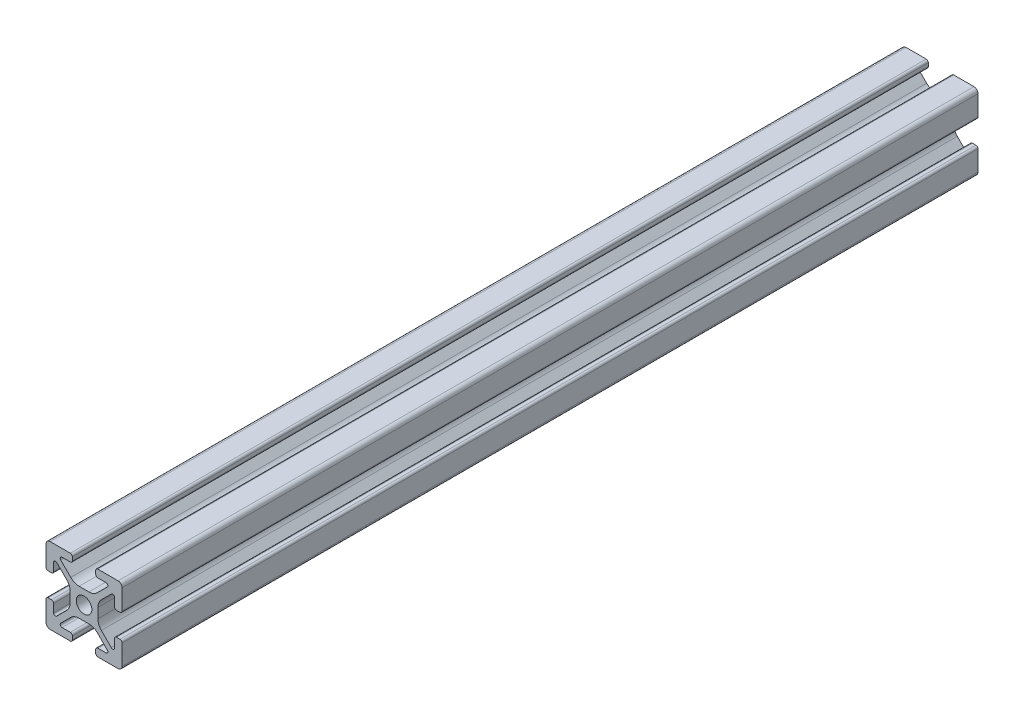
SolidWorks part; units mm, degrees
ref_plane "Front Plane" through (0, 0, 0) normal (0, 0, 1) x (1, 0, 0)
ref_plane "Top Plane" through (0, 0, 0) normal (0, 1, 0) x (1, 0, 0)
ref_plane "Right Plane" through (0, 0, 0) normal (1, 0, 0) x (0, 0, -1)
sketch "Sketch1" plane through (0, 0, 0) normal (0, 0, 1) x (1, 0, 0)
  line L0 (-3.6422, 1.2878) -> (-3.6422, -1.2878)
  line L1 (-1.2878, 3.6422) -> (1.2878, 3.6422)
  line L2 (-9.4433, 3.069) -> (-8.553, 3.069)
  line L3 (0, 0) -> (-15.7854, 0) construction
  line L4 (-3.4964, 4.5571) -> (-6.1213, 7.182)
  line L5 (-3.622, 8) -> (-5.7825, 8)
  line L6 (-3.069, 9.4433) -> (-3.069, 8.553)
  line L7 (-3.622, 10) -> (-8.939, 10)
  line L8 (0, 0) -> (0, 15.0393) construction
  line L9 (10, 3.622) -> (10, 8.939)
  line L10 (8, 3.622) -> (8, 5.7825)
  line L11 (4.5571, 3.4964) -> (7.182, 6.1213)
  line L12 (3.622, 10) -> (8.939, 10)
  line L13 (3.069, 9.4433) -> (3.069, 8.553)
  line L14 (3.622, 8) -> (5.7825, 8)
  line L15 (3.4964, 4.5571) -> (6.1213, 7.182)
  line L16 (9.4433, 3.069) -> (8.553, 3.069)
  line L17 (3.6422, 1.2878) -> (3.6422, -1.2878)
  line L18 (-10, -3.622) -> (-10, -8.939)
  line L19 (-8, -3.622) -> (-8, -5.7825)
  line L20 (-4.5571, -3.4964) -> (-7.182, -6.1213)
  line L21 (9.4433, -3.069) -> (8.553, -3.069)
  line L22 (3.4964, -4.5571) -> (6.1213, -7.182)
  line L23 (3.622, -8) -> (5.7825, -8)
  line L24 (3.069, -9.4433) -> (3.069, -8.553)
  line L25 (3.622, -10) -> (8.939, -10)
  line L26 (4.5571, -3.4964) -> (7.182, -6.1213)
  line L27 (8, -3.622) -> (8, -5.7825)
  line L28 (10, -3.622) -> (10, -8.939)
  line L29 (-3.622, -10) -> (-8.939, -10)
  line L30 (-3.069, -9.4433) -> (-3.069, -8.553)
  line L31 (-3.622, -8) -> (-5.7825, -8)
  line L32 (-3.4964, -4.5571) -> (-6.1213, -7.182)
  line L33 (-9.4433, -3.069) -> (-8.553, -3.069)
  line L34 (-1.2878, -3.6422) -> (1.2878, -3.6422)
  line L48 (-4.5571, 3.4964) -> (-7.182, 6.1213)
  line L49 (-8, 3.622) -> (-8, 5.7825)
  line L52 (-10, 3.622) -> (-10, 8.939)
  arc A0 (-8.553, 3.069) -> (-8, 3.622) centre (-8.553, 3.622) ccw
  arc A1 (-8, 5.7825) -> (-7.182, 6.1213) centre (-7.5208, 5.7825) cw
  arc A2 (-4.5571, 3.4964) -> (-3.6422, 1.2878) centre (-6.7657, 1.2878) cw
  arc A3 (-3.4964, 4.5571) -> (-1.2878, 3.6422) centre (-1.2878, 6.7657) ccw
  arc A4 (-5.7825, 8) -> (-6.1213, 7.182) centre (-5.7825, 7.5208) ccw
  arc A5 (-3.622, 10) -> (-3.069, 9.4433) centre (-3.622, 9.447) cw
  arc A6 (-3.069, 8.553) -> (-3.622, 8) centre (-3.622, 8.553) cw
  arc A7 (8.939, 10) -> (10, 8.939) centre (8.939, 8.939) cw
  arc A8 (10, 3.622) -> (9.4433, 3.069) centre (9.447, 3.622) cw
  arc A9 (3.069, 8.553) -> (3.622, 8) centre (3.622, 8.553) ccw
  arc A10 (3.622, 10) -> (3.069, 9.4433) centre (3.622, 9.447) ccw
  arc A11 (5.7825, 8) -> (6.1213, 7.182) centre (5.7825, 7.5208) cw
  arc A12 (3.4964, 4.5571) -> (1.2878, 3.6422) centre (1.2878, 6.7657) cw
  arc A13 (4.5571, 3.4964) -> (3.6422, 1.2878) centre (6.7657, 1.2878) ccw
  arc A14 (8, 5.7825) -> (7.182, 6.1213) centre (7.5208, 5.7825) ccw
  arc A15 (8.553, 3.069) -> (8, 3.622) centre (8.553, 3.622) cw
  arc A16 (-8.939, -10) -> (-10, -8.939) centre (-8.939, -8.939) cw
  arc A17 (-10, -3.622) -> (-9.4433, -3.069) centre (-9.447, -3.622) cw
  arc A18 (8.553, -3.069) -> (8, -3.622) centre (8.553, -3.622) ccw
  arc A19 (8, -5.7825) -> (7.182, -6.1213) centre (7.5208, -5.7825) cw
  arc A20 (4.5571, -3.4964) -> (3.6422, -1.2878) centre (6.7657, -1.2878) cw
  arc A21 (3.4964, -4.5571) -> (1.2878, -3.6422) centre (1.2878, -6.7657) ccw
  arc A22 (5.7825, -8) -> (6.1213, -7.182) centre (5.7825, -7.5208) ccw
  arc A23 (3.622, -10) -> (3.069, -9.4433) centre (3.622, -9.447) cw
  arc A24 (3.069, -8.553) -> (3.622, -8) centre (3.622, -8.553) cw
  arc A25 (10, -3.622) -> (9.4433, -3.069) centre (9.447, -3.622) ccw
  arc A26 (8.939, -10) -> (10, -8.939) centre (8.939, -8.939) ccw
  arc A27 (-3.069, -8.553) -> (-3.622, -8) centre (-3.622, -8.553) ccw
  arc A28 (-3.622, -10) -> (-3.069, -9.4433) centre (-3.622, -9.447) ccw
  arc A29 (-5.7825, -8) -> (-6.1213, -7.182) centre (-5.7825, -7.5208) cw
  arc A30 (-3.4964, -4.5571) -> (-1.2878, -3.6422) centre (-1.2878, -6.7657) cw
  arc A31 (-4.5571, -3.4964) -> (-3.6422, -1.2878) centre (-6.7657, -1.2878) ccw
  arc A32 (-8, -5.7825) -> (-7.182, -6.1213) centre (-7.5208, -5.7825) ccw
  arc A33 (-8.553, -3.069) -> (-8, -3.622) centre (-8.553, -3.622) cw
  arc A51 (-10, 3.622) -> (-9.4433, 3.069) centre (-9.447, 3.622) ccw
  arc A56 (-8.939, 10) -> (-10, 8.939) centre (-8.939, 8.939) ccw
  circle A57 centre (0, 0) radius 2.05
  point P1 (-3.6422, 0)
  point P46 (0, 0)
  point P48 (0, 0)
  point P53 (0, 3.6422)
  point P60 (0, 0)
  point P61 (0, 0)
  point P62 (0, 0)
  point P74 (0, 0)
  point P85 (0, 0)
  point P87 (0, 0)
  point P99 (0, 0)
  point P101 (0, 0)
  point P102 (0, 0)
  point P116 (0, -3.6422)
  point P117 (3.6422, 0)
  point P123 (0, 0)
  point P125 (0, 0)
  point P127 (0, 0)
  point P139 (0, 0)
  point P140 (0, 0)
  point P141 (0, 0)
  point P142 (0, 0)
  point P179 (0, 0)
  point P192 (0, 0)
  point P193 (0, 0)
  dimension "D1" = 0.553
  dimension "D3" = 3.1235
  dimension "D4" = 0.553
  dimension "D2" = 0.4792
  dimension "D9" = 3.4964
  dimension "D10" = 3.6422
  dimension "D11" = 4.5571
  dimension "D12" = 5.7825
  dimension "D13" = 9.4433
  dimension "D5" = 1.061
  dimension "D6" = 2.05
  dimension "D7" = 1.2878
  dimension "D8" = 3.069
extrude "Boss-Extrude1" add sketch "Sketch1" against normal blind 225
